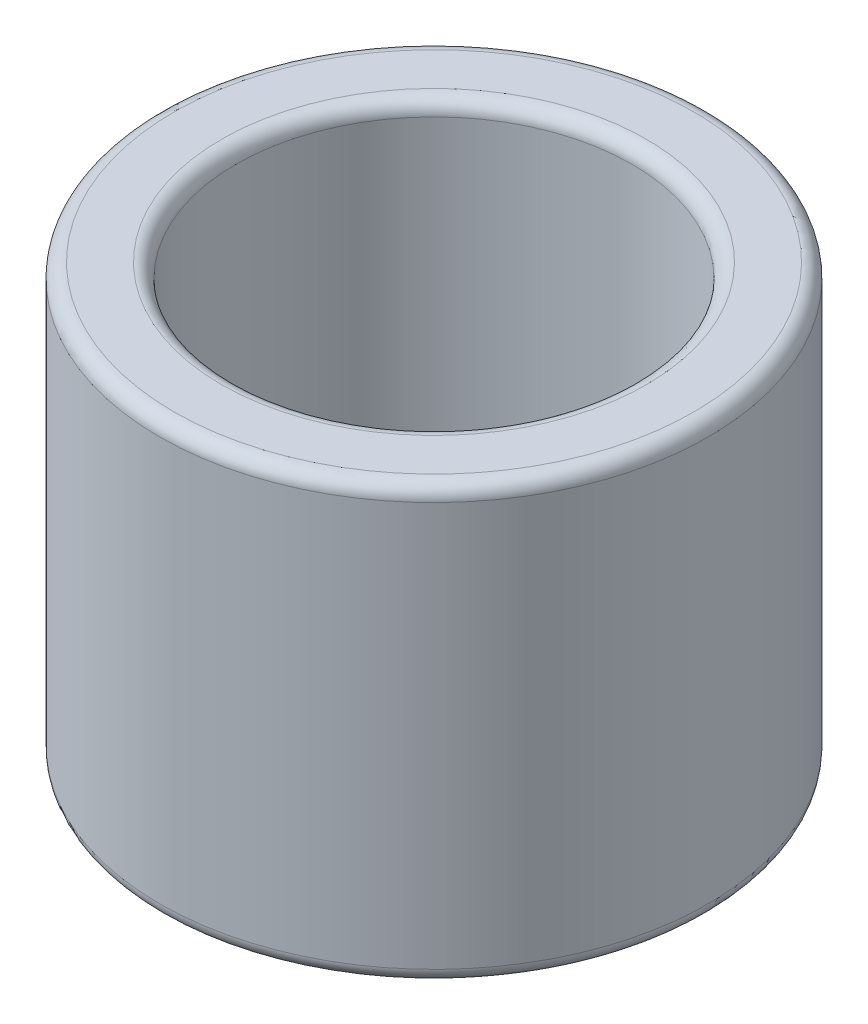
SolidWorks part; units mm, degrees
ref_plane "Front Plane" through (0, 0, 0) normal (0, 0, 1) x (1, 0, 0)
ref_plane "Top Plane" through (0, 0, 0) normal (0, 1, 0) x (1, 0, 0)
ref_plane "Right Plane" through (0, 0, 0) normal (1, 0, 0) x (0, 0, -1)
sketch "Sketch1" plane through (0, 0, 0) normal (0, 1, 0) x (1, 0, 0)
  circle A0 centre (0, 0) radius 48.26
extrude "Boss-Extrude1" add sketch "Sketch1" along normal mid plane 76.2 contours A0
sketch "Sketch3" plane through (0, 38.1, 0) normal (0, 1, 0) x (1, 0, 0)
  circle A0 centre (0, 0) radius 34.8444
extrude "Cut-Extrude2" cut sketch "Sketch3" against normal blind 50.8
fillet "Fillet1" radius 2.54 3 edges at (0, -38.1, 48.26) (0, 38.1, 48.26) (0, 38.1, 34.8444)
